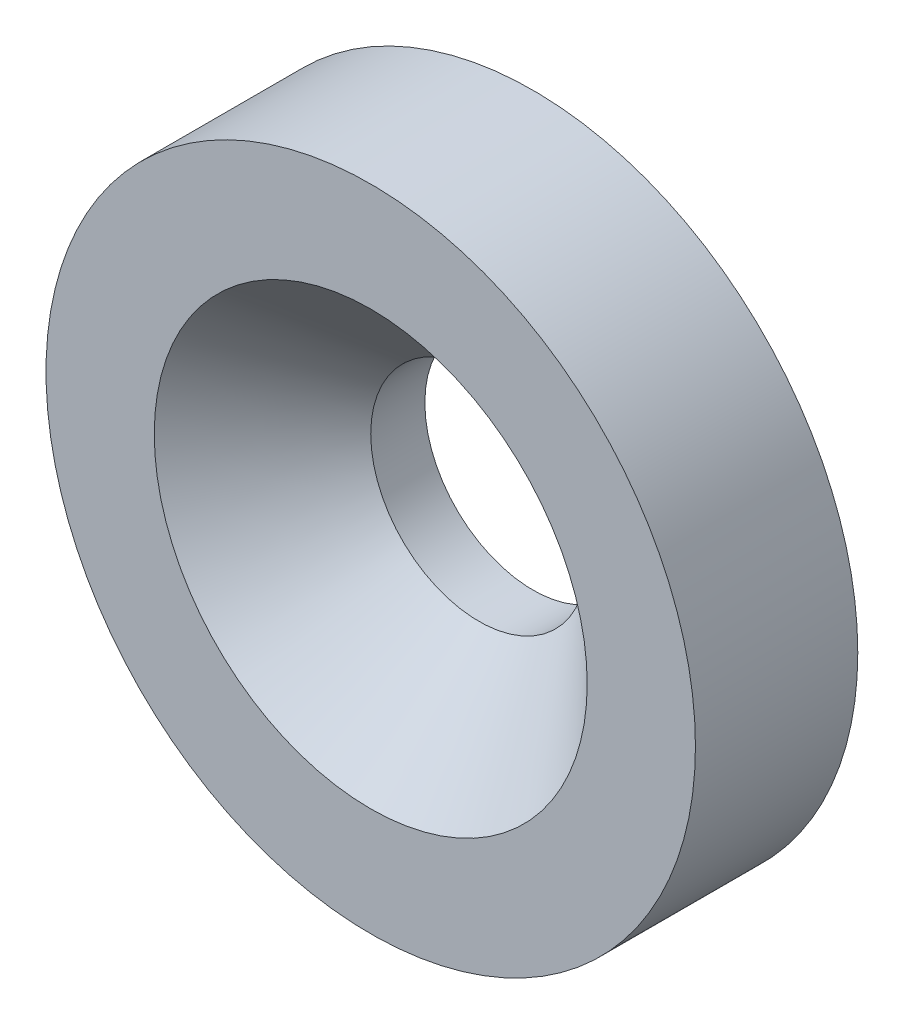
SolidWorks part; units mm, degrees
ref_plane "前视基准面" through (0, 0, 0) normal (0, 0, 1) x (1, 0, 0)
ref_plane "上视基准面" through (0, 0, 0) normal (0, 1, 0) x (1, 0, 0)
ref_plane "右视基准面" through (0, 0, 0) normal (1, 0, 0) x (0, 0, -1)
sketch "草图1" plane through (0, 0, 0) normal (0, 0, 1) x (1, 0, 0)
  circle A0 centre (0, 0) radius 6
  dimension "D1" = 12
extrude "凸台-拉伸1" add sketch "草图1" along normal blind 3
sketch "草图2" plane through (0, 0, 3) normal (0, 0, 1) x (1, 0, 0)
  circle A0 centre (0, 0) radius 2
  dimension "D1" = 4
extrude "切除-拉伸1" cut sketch "草图2" against normal blind 3
chamfer "倒角1" distance 2 angle 45 1 edges at (2, 0, 3)
